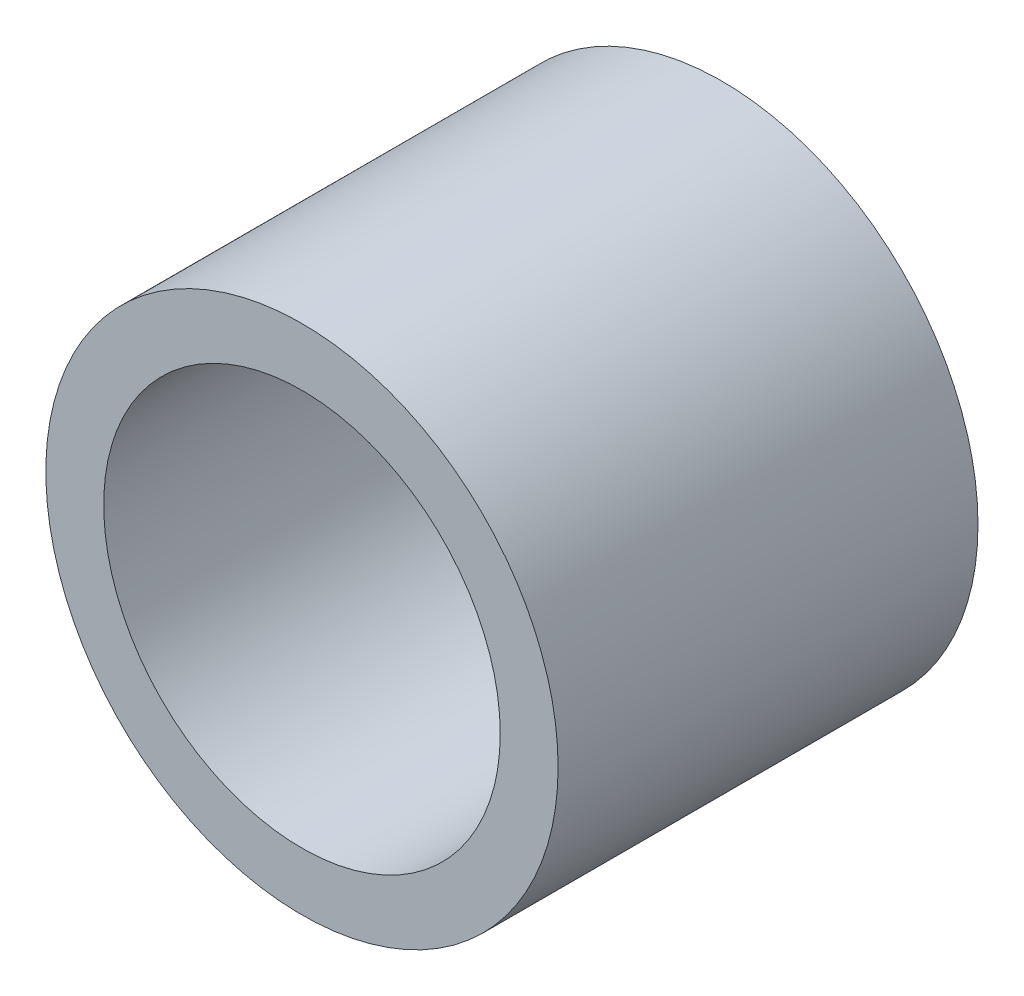
SolidWorks part; units mm, degrees
material "AISI 304"
ref_plane "Front Plane" through (0, 0, 0) normal (0, 0, 1) x (1, 0, 0)
ref_plane "Top Plane" through (0, 0, 0) normal (0, 1, 0) x (1, 0, 0)
ref_plane "Right Plane" through (0, 0, 0) normal (1, 0, 0) x (0, 0, -1)
sketch "Sketch1" plane through (0, 0, 0) normal (0, 1, 0) x (1, 0, 0)
  line L0 (0, 0) -> (0, 45.9553) construction
  line L1 (-10.98, 0) -> (-10.98, 18)
  line L2 (-8.5, 0) -> (-8.5, 18)
  line L3 (-8.5, 18) -> (-10.98, 18)
  line L4 (-10.98, 0) -> (-8.5, 0)
  point P1 (-10.98, 0)
  point P4 (-10.98, 18)
  point P7 (-8.5, 0)
  point P8 (-8.5, 18)
revolve "Revolve1" add sketch "Sketch1" angle 360 about L0
